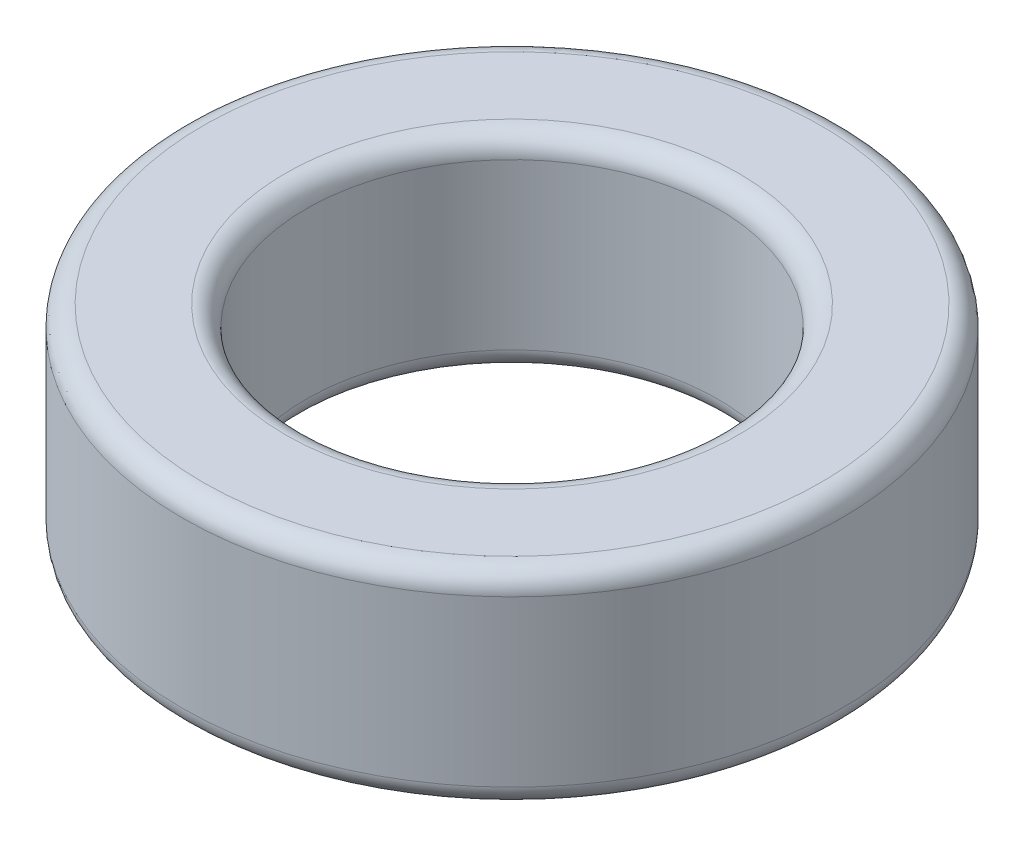
SolidWorks part; units mm, degrees
material "合金鋼"
ref_plane "前基準面" through (0, 0, 0) normal (0, 0, 1) x (1, 0, 0)
ref_plane "上基準面" through (0, 0, 0) normal (0, 1, 0) x (1, 0, 0)
ref_plane "右基準面" through (0, 0, 0) normal (1, 0, 0) x (0, 0, -1)
sketch "草圖1" plane through (0, 0, 0) normal (0, 1, 0) x (1, 0, 0)
  circle A0 centre (0, 0) radius 8
  circle A1 centre (0, 0) radius 5
  dimension "D1" = 16
  dimension "D2" = 10
extrude "填料-伸長1" add sketch "草圖1" along normal blind 5
fillet "圓角1" radius 0.5 4 edges at (0, 0, 8) (0, 0, 5) (0, 5, 5) (0, 5, 8)
